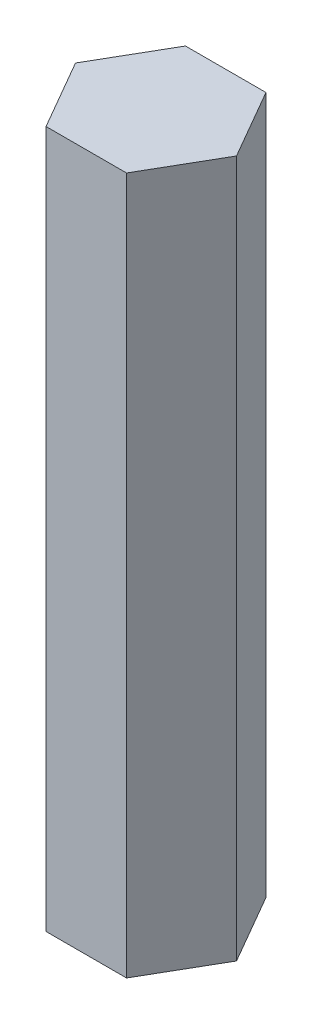
SolidWorks part; units mm, degrees
material "보통 탄소강"
ref_plane "Front" through (0, 0, 0) normal (0, 0, 1) x (1, 0, 0)
ref_plane "Top" through (0, 0, 0) normal (0, 1, 0) x (1, 0, 0)
ref_plane "Right" through (0, 0, 0) normal (1, 0, 0) x (0, 0, -1)
sketch "Sketch1" plane through (0, 0, 0) normal (0, 1, 0) x (1, 0, 0)
  line L1 (-5.7735, 10) -> (-11.547, 0)
  line L2 (-11.547, 0) -> (-5.7735, -10)
  line L3 (-5.7735, -10) -> (5.7735, -10)
  line L4 (5.7735, -10) -> (11.547, 0)
  line L5 (11.547, 0) -> (5.7735, 10)
  line L6 (5.7735, 10) -> (-5.7735, 10)
  circle A0 centre (0, 0) radius 10 construction
  dimension "D1" = 20
extrude "Extrude1" add sketch "Sketch1" along normal blind 100
equation "\"D\" = 20mm"
equation "\"H\" = 100mm"
equation "\"D1@Sketch1\"= \"D\""
equation "\"D1@Extrude1\"= \"H\""
